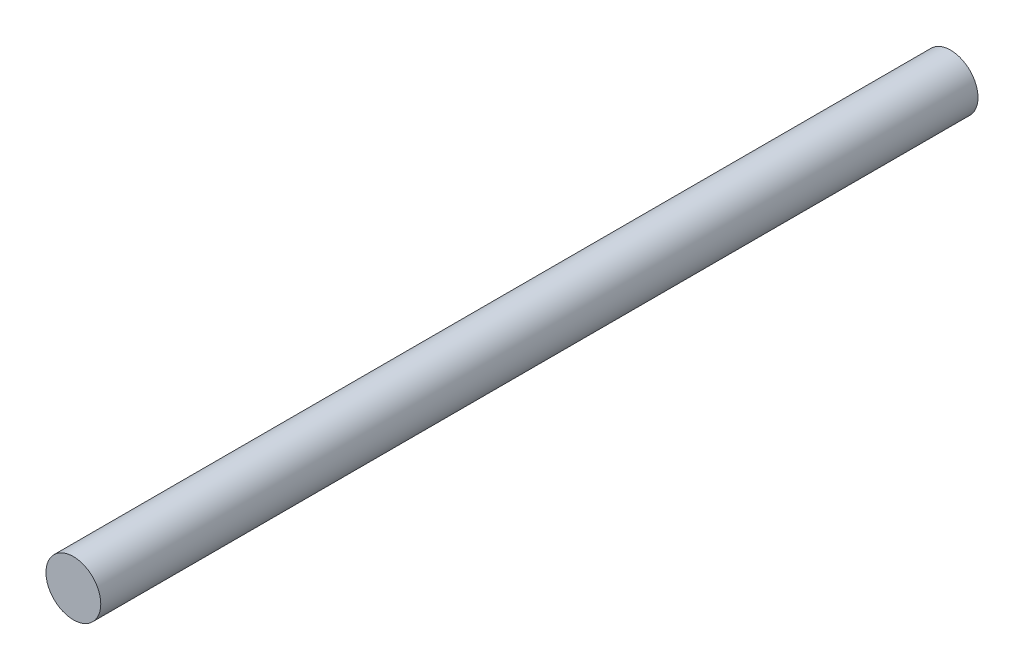
SolidWorks part; units mm, degrees
ref_plane "Front Plane" through (0, 0, 0) normal (0, 0, 1) x (1, 0, 0)
ref_plane "Top Plane" through (0, 0, 0) normal (0, 1, 0) x (1, 0, 0)
ref_plane "Right Plane" through (0, 0, 0) normal (1, 0, 0) x (0, 0, -1)
sketch "Sketch1" plane through (0, 0, 0) normal (0, 0, 1) x (1, 0, 0)
  circle A0 centre (0, 0) radius 6.35
  dimension "D1" = 12.7
extrude "Boss-Extrude1" add sketch "Sketch1" along normal blind 203.2
